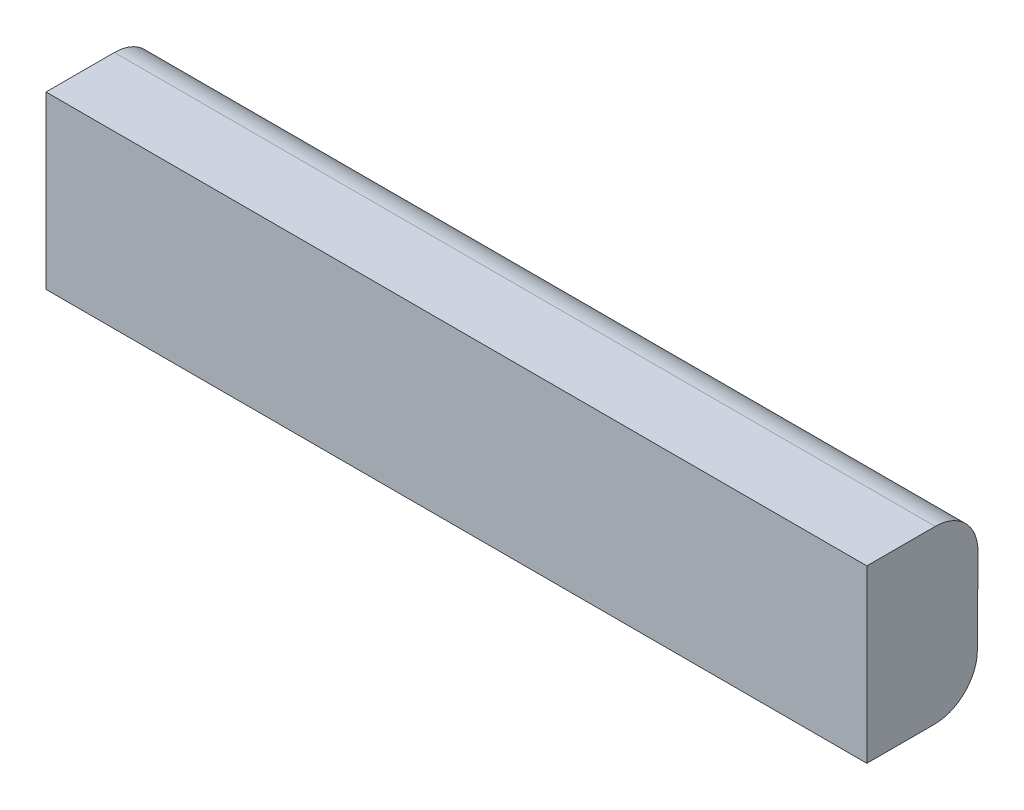
SolidWorks part; units mm, degrees
ref_plane "Front Plane" through (0, 0, 0) normal (0, 0, 1) x (1, 0, 0)
ref_plane "Top Plane" through (0, 0, 0) normal (0, 1, 0) x (1, 0, 0)
ref_plane "Right Plane" through (0, 0, 0) normal (1, 0, 0) x (0, 0, -1)
sketch "Sketch1" plane through (0, 0, 0) normal (1, 0, 0) x (0, 0, -1)
  line L0 (-17.1423, 84.1796) -> (-67.9423, 84.1796)
  line L1 (-67.9423, -42.8204) -> (-67.9423, 84.1796)
  line L2 (-67.9423, -42.8204) -> (-17.6191, -42.8204)
  line L3 (14.6077, 52.4296) -> (14.1309, -11.0704)
  arc A1 (-17.1423, 84.1796) -> (14.6077, 52.4296) centre (-17.1423, 52.4296) cw
  arc A2 (-17.6191, -42.8204) -> (14.1309, -11.0704) centre (-17.6191, -11.0704) ccw
  dimension "D3" = 63.5
  dimension "D4" = 31.75
  dimension "D1" = 50.8
  dimension "D2" = 127
  dimension "D5" = 31.75
  dimension "D6" = 31.75
  dimension "D7" = 31.75
  dimension "D8" = 31.75
extrude "Boss-Extrude1" add sketch "Sketch1" along normal blind 609.6
